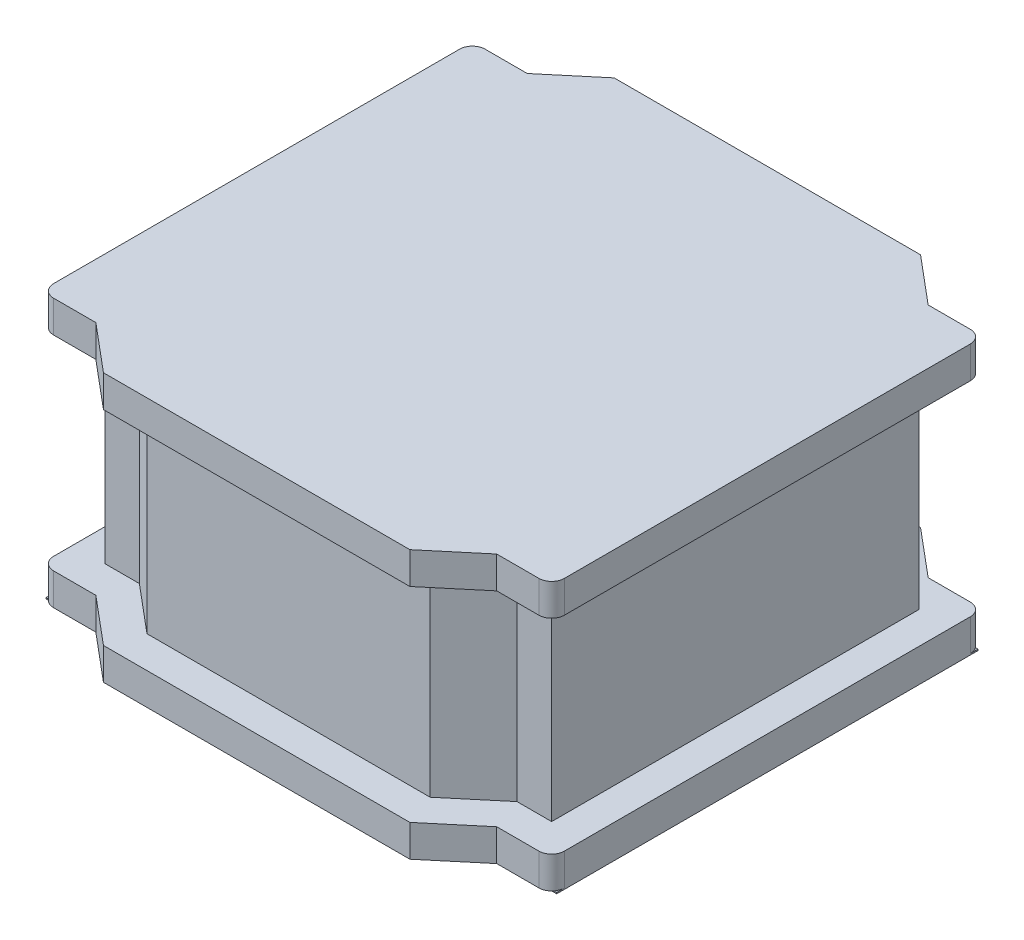
SolidWorks part; units mm, degrees
ref_plane "Alzado" through (0, 0, 0) normal (0, 0, 1) x (1, 0, 0)
ref_plane "Planta" through (0, 0, 0) normal (0, 1, 0) x (1, 0, 0)
ref_plane "Vista lateral" through (0, 0, 0) normal (1, 0, 0) x (0, 0, -1)
sketch "Croquis1" plane through (0, 0, 0) normal (0, 1, 0) x (1, 0, 0)
  line L0 (0.0879, 2.3156) -> (0.0879, -1.9186) construction
  line L1 (-3.3874, 0) -> (5.3457, 0) construction
  line L2 (1.2879, 2) -> (-1.1121, 2)
  line L3 (-1.1121, 2) -> (-1.4821, 1.6895)
  line L4 (-1.4821, 1.6895) -> (-1.8121, 1.6895)
  line L5 (-1.9121, 1.5895) -> (-1.9121, -1.5895)
  line L6 (2.0879, 1.5895) -> (2.0879, -1.5895)
  line L7 (1.658, 1.6895) -> (1.9879, 1.6895)
  line L8 (1.2879, 2) -> (1.658, 1.6895)
  line L9 (1.2879, -2) -> (1.658, -1.6895)
  line L10 (1.658, -1.6895) -> (1.9879, -1.6895)
  line L11 (-1.4821, -1.6895) -> (-1.8121, -1.6895)
  line L12 (-1.1121, -2) -> (-1.4821, -1.6895)
  line L13 (1.2879, -2) -> (-1.1121, -2)
  arc A0 (-1.8121, -1.6895) -> (-1.9121, -1.5895) centre (-1.8121, -1.5895) cw
  arc A1 (1.9879, -1.6895) -> (2.0879, -1.5895) centre (1.9879, -1.5895) ccw
  arc A2 (2.0879, 1.5895) -> (1.9879, 1.6895) centre (1.9879, 1.5895) ccw
  arc A3 (-1.8121, 1.6895) -> (-1.9121, 1.5895) centre (-1.8121, 1.5895) ccw
  point P14 (0.0879, 2)
  point P17 (2.0879, 0)
  point P18 (-1.9121, 0)
  point P20 (0.0879, -2)
  point P23 (-1.9121, -1.6895)
  point P26 (2.0879, -1.6895)
  point P29 (2.0879, 1.6895)
  point P32 (-1.9121, 1.6895)
  dimension "D5" = 0.1
  dimension "D1" = 2
  dimension "D2" = 2
  dimension "D3" = 40
  dimension "D4" = 1.2
extrude "Saliente-Extruir1" add sketch "Croquis1" along normal blind 0.25
sketch "Croquis3" plane through (0, 0.25, 0) normal (0, 1, 0) x (1, 0, 0)
  line L24 (-1.0211, -1.75) -> (1.1969, -1.75)
  line L25 (1.1969, -1.75) -> (1.567, -1.4395)
  line L26 (1.567, -1.4395) -> (1.8379, -1.4395)
  line L27 (1.8379, -1.4395) -> (1.8379, 1.4395)
  line L28 (1.8379, 1.4395) -> (1.567, 1.4395)
  line L29 (1.567, 1.4395) -> (1.1969, 1.75)
  line L30 (1.1969, 1.75) -> (-1.0211, 1.75)
  line L31 (-1.0211, 1.75) -> (-1.3911, 1.4395)
  line L32 (-1.3911, 1.4395) -> (-1.6621, 1.4395)
  line L33 (-1.6621, 1.4395) -> (-1.6621, -1.4395)
  line L34 (-1.6621, -1.4395) -> (-1.3911, -1.4395)
  line L35 (-1.3911, -1.4395) -> (-1.0211, -1.75)
  line L36 (-1.0211, -1.75) -> (1.1969, -1.75)
  line L37 (1.1969, -1.75) -> (1.567, -1.4395)
  line L38 (1.567, -1.4395) -> (1.8379, -1.4395)
  line L39 (1.8379, -1.4395) -> (1.8379, 1.4395)
  line L40 (1.8379, 1.4395) -> (1.567, 1.4395)
  line L41 (1.567, 1.4395) -> (1.1969, 1.75)
  line L42 (1.1969, 1.75) -> (-1.0211, 1.75)
  line L43 (-1.0211, 1.75) -> (-1.3911, 1.4395)
  line L44 (-1.3911, 1.4395) -> (-1.6621, 1.4395)
  line L45 (-1.6621, 1.4395) -> (-1.6621, -1.4395)
  line L46 (-1.6621, -1.4395) -> (-1.3911, -1.4395)
  line L47 (-1.3911, -1.4395) -> (-1.0211, -1.75)
  dimension "D1" = 0.25
extrude "Saliente-Extruir3" add sketch "Croquis3" along normal blind 1.6
ref_plane "Plano1" through (0, 2.1, 0) normal (0, 1, 0) x (1, 0, 0)
sketch "Croquis2" plane through (0, 2.1, 0) normal (0, 1, 0) x (1, 0, 0)
  line L12 (-1.1121, -2) -> (1.2879, -2)
  line L13 (1.2879, -2) -> (1.658, -1.6895)
  line L14 (1.658, -1.6895) -> (1.9879, -1.6895)
  line L15 (2.0879, -1.5895) -> (2.0879, 1.5895)
  line L16 (1.9879, 1.6895) -> (1.658, 1.6895)
  line L17 (1.658, 1.6895) -> (1.2879, 2)
  line L18 (1.2879, 2) -> (-1.1121, 2)
  line L19 (-1.1121, 2) -> (-1.4821, 1.6895)
  line L20 (-1.4821, 1.6895) -> (-1.8121, 1.6895)
  line L21 (-1.9121, 1.5895) -> (-1.9121, -1.5895)
  line L22 (-1.8121, -1.6895) -> (-1.4821, -1.6895)
  line L23 (-1.4821, -1.6895) -> (-1.1121, -2)
  line L24 (-1.1121, -2) -> (1.2879, -2)
  line L25 (1.2879, -2) -> (1.658, -1.6895)
  line L26 (1.658, -1.6895) -> (1.9879, -1.6895)
  line L27 (2.0879, -1.5895) -> (2.0879, 1.5895)
  line L28 (1.9879, 1.6895) -> (1.658, 1.6895)
  line L29 (1.658, 1.6895) -> (1.2879, 2)
  line L30 (1.2879, 2) -> (-1.1121, 2)
  line L31 (-1.1121, 2) -> (-1.4821, 1.6895)
  line L32 (-1.4821, 1.6895) -> (-1.8121, 1.6895)
  line L33 (-1.9121, 1.5895) -> (-1.9121, -1.5895)
  line L34 (-1.8121, -1.6895) -> (-1.4821, -1.6895)
  line L35 (-1.4821, -1.6895) -> (-1.1121, -2)
  arc A4 (1.9879, -1.6895) -> (2.0879, -1.5895) centre (1.9879, -1.5895) ccw
  arc A5 (1.9879, -1.6895) -> (2.0879, -1.5895) centre (1.9879, -1.5895) ccw
  arc A6 (2.0879, 1.5895) -> (1.9879, 1.6895) centre (1.9879, 1.5895) ccw
  arc A7 (2.0879, 1.5895) -> (1.9879, 1.6895) centre (1.9879, 1.5895) ccw
  arc A8 (-1.8121, 1.6895) -> (-1.9121, 1.5895) centre (-1.8121, 1.5895) ccw
  arc A9 (-1.8121, 1.6895) -> (-1.9121, 1.5895) centre (-1.8121, 1.5895) ccw
  arc A10 (-1.9121, -1.5895) -> (-1.8121, -1.6895) centre (-1.8121, -1.5895) ccw
  arc A11 (-1.9121, -1.5895) -> (-1.8121, -1.6895) centre (-1.8121, -1.5895) ccw
  dimension "D1" = 0
extrude "Saliente-Extruir2" add sketch "Croquis2" against normal blind 0.25 separate body
sketch "Croquis4" plane through (0, 0, 0) normal (0, -1, 0) x (1, 0, 0)
  line L0 (0.0879, 1.1918) -> (0.0879, -0.8163) construction
  line L1 (2.0879, -1.65) -> (1.0879, -1.65)
  line L2 (2.0879, -1.65) -> (2.0879, 1.65)
  line L3 (2.0879, 1.65) -> (1.0879, 1.65)
  line L4 (1.0879, -1.65) -> (1.0879, 1.65)
  line L5 (0, 0) -> (2.5141, 0) construction
  line L6 (-1.9121, 1.65) -> (-0.9121, 1.65)
  line L7 (-0.9121, -1.65) -> (-0.9121, 1.65)
  line L8 (-1.9121, -1.65) -> (-0.9121, -1.65)
  line L9 (-1.9121, -1.65) -> (-1.9121, 1.65)
  dimension "D1" = 3.3
  dimension "D2" = 1
  dimension "D3" = 2
extrude "Saliente-Extruir4" add sketch "Croquis4" along normal blind 0.01
